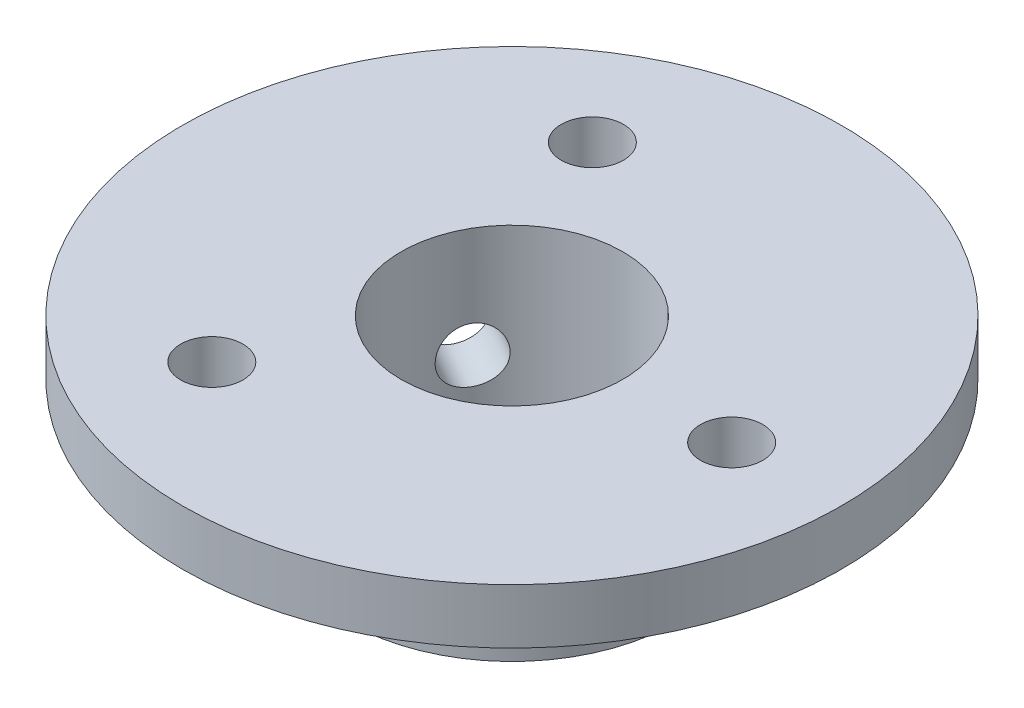
SolidWorks part; units mm, degrees
other "Metal Wheel Hub"
ref_plane "Front Plane" through (0, 0, 0) normal (0, 0, 1) x (1, 0, 0)
ref_plane "Top Plane" through (0, 0, 0) normal (0, 1, 0) x (1, 0, 0)
ref_plane "Right Plane" through (0, 0, 0) normal (1, 0, 0) x (0, 0, -1)
sketch3d "Hub neck sketch datum points"
  point P0 (-19.0092, -273, -53.2449)
  point P1 (-9.0092, -273, -53.2449)
  point P2 (-19.0092, -273, -63.2449)
ref_plane "Hub neck sketch plane" through (0, -273, 0) normal (0, 1, 0) x (1, 0, 0)
sketch "Hub neck sketch" plane through (0, -273, 0) normal (0, 1, 0) x (1, 0, 0)
  circle A0 centre (-19.0092, 53.2449) radius 9
extrude "Hub neck" add sketch "Hub neck sketch" along normal blind 10 separate body
sketch3d "Rim clamp flange sketch datum points"
  point P0 (-19.0092, -266, -53.2449)
  point P1 (-9.0092, -266, -53.2449)
  point P2 (-19.0092, -266, -63.2449)
ref_plane "Rim clamp flange sketch plane" through (0, -266, 0) normal (0, 1, 0) x (1, 0, 0)
sketch "Rim clamp flange sketch" plane through (0, -266, 0) normal (0, 1, 0) x (1, 0, 0)
  circle A0 centre (-19.0092, 53.2449) radius 18
extrude "Rim clamp flange" add sketch "Rim clamp flange sketch" along normal blind 3
sketch3d "Axle clearance sketch datum points"
  point P0 (-19.0092, -273.1, -53.2449)
  point P1 (-9.0092, -273.1, -53.2449)
  point P2 (-19.0092, -273.1, -63.2449)
ref_plane "Axle clearance sketch plane" through (0, -273.1, 0) normal (0, 1, 0) x (1, 0, 0)
sketch "Axle clearance sketch" plane through (0, -273.1, 0) normal (0, 1, 0) x (1, 0, 0)
  circle A0 centre (-19.0092, 53.2449) radius 6.05
extrude "Axle clearance" cut sketch "Axle clearance sketch" along normal blind 10.2
sketch3d "Rim bolt clearance pattern sketch datum points"
  point P0 (-19.0092, -266.1, -53.2449)
  point P1 (-9.0092, -266.1, -53.2449)
  point P2 (-19.0092, -266.1, -63.2449)
ref_plane "Rim bolt clearance pattern sketch plane" through (0, -266.1, 0) normal (0, 1, 0) x (1, 0, 0)
sketch "Rim bolt clearance pattern sketch" plane through (0, -266.1, 0) normal (0, 1, 0) x (1, 0, 0)
  circle A0 centre (-7.0092, 53.2449) radius 1.7
  circle A1 centre (-25.0092, 42.8526) radius 1.7
  circle A2 centre (-25.0092, 63.6372) radius 1.7
extrude "Rim bolt clearance pattern" cut sketch "Rim bolt clearance pattern sketch" along normal blind 3.2
sketch3d "Positive hub pin bore sketch datum points"
  point P0 (-27.6694, -269, -58.2449)
  point P1 (-22.6694, -269, -66.9051)
  point P2 (-27.6694, -259, -58.2449)
ref_plane "Positive hub pin bore sketch plane" through (-45.9729, 0, -26.5424) normal (0.866, 0, 0.5) x (0.5, 0, -0.866)
sketch "Positive hub pin bore sketch" plane through (-45.9729, 0, -26.5424) normal (0.866, 0, 0.5) x (0.5, 0, -0.866)
  circle A0 centre (36.6068, -269) radius 1.5
extrude "Positive hub pin bore" cut sketch "Positive hub pin bore sketch" along normal blind 20
